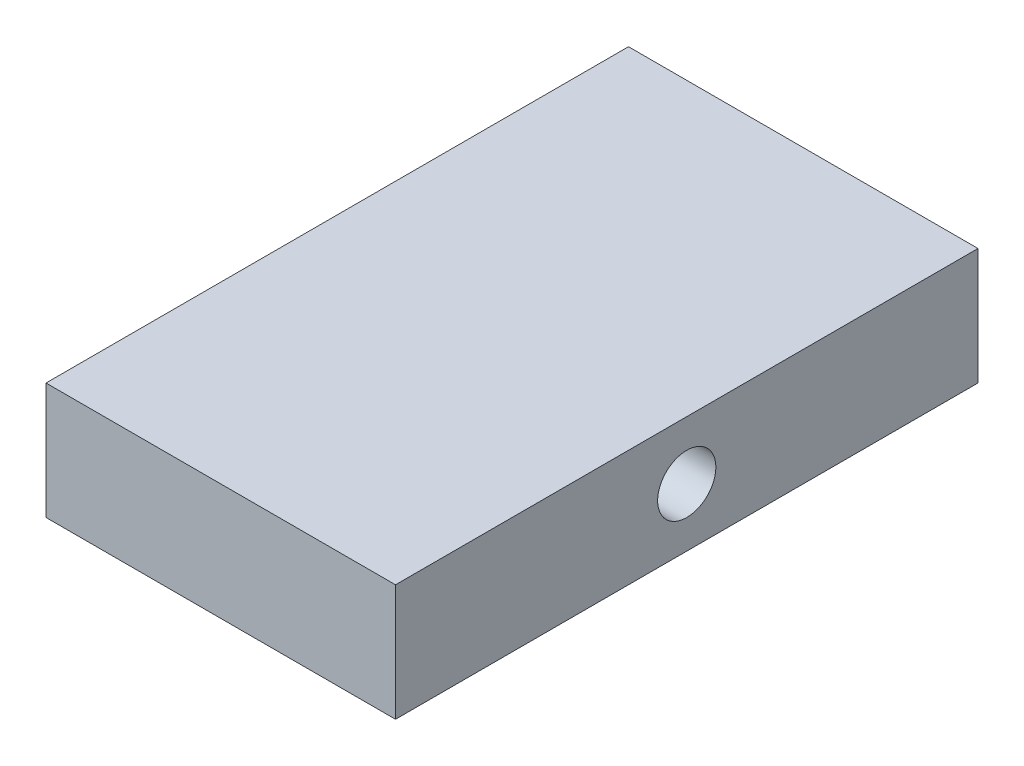
SolidWorks part; units mm, degrees
ref_plane "Front Plane" through (0, 0, 0) normal (0, 0, 1) x (1, 0, 0)
ref_plane "Top Plane" through (0, 0, 0) normal (0, 1, 0) x (1, 0, 0)
ref_plane "Right Plane" through (0, 0, 0) normal (1, 0, 0) x (0, 0, -1)
sketch "Sketch2" plane through (0, 0, 0) normal (1, 0, 0) x (0, 0, -1)
  line L1 (63.5, -12.7) -> (-63.5, -12.7)
  line L2 (63.5, -12.7) -> (63.5, 12.7)
  line L3 (63.5, 12.7) -> (-63.5, 12.7)
  line L4 (-63.5, -12.7) -> (-63.5, 12.7)
  line L5 (63.5, -12.7) -> (-63.5, 12.7) construction
  line L6 (63.5, 12.7) -> (-63.5, -12.7) construction
  point P0 (0, 0)
  dimension "D1" = 127
  dimension "D2" = 25.4
extrude "Boss-Extrude1" add sketch "Sketch2" along normal blind 76.2
sketch "Sketch3" plane through (76.2, 0, 0) normal (1, 0, 0) x (0, 0, -1)
  circle A0 centre (0, 0) radius 6.35
extrude "Cut-Extrude1" cut sketch "Sketch3" against normal blind 63.5
